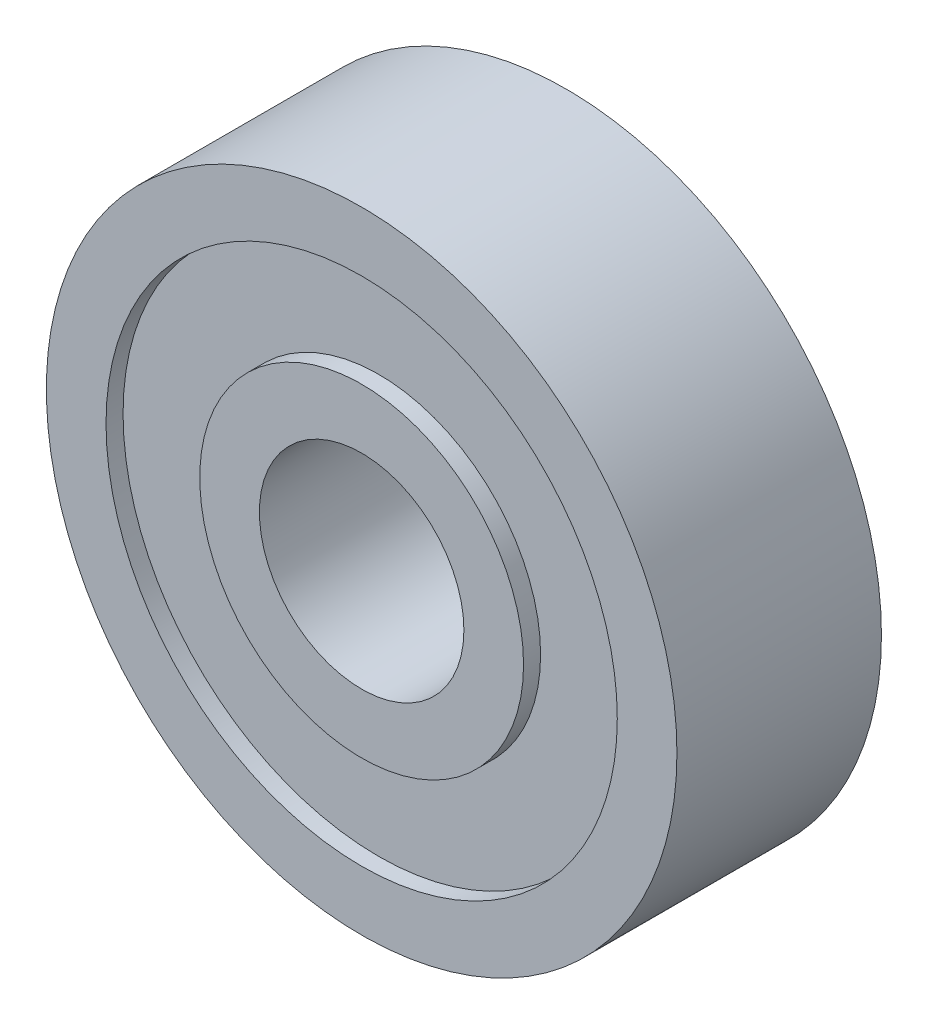
SolidWorks part; units mm, degrees
material "AISI Type 316L stainless steel"
ref_plane "Front Plane" through (0, 0, 0) normal (0, 0, 1) x (1, 0, 0)
ref_plane "Top Plane" through (0, 0, 0) normal (0, 1, 0) x (1, 0, 0)
ref_plane "Right Plane" through (0, 0, 0) normal (1, 0, 0) x (0, 0, -1)
sketch "Sketch1" plane through (0, 0, 0) normal (0, 0, 1) x (1, 0, 0)
  circle A1 centre (0, 0) radius 18.5
  dimension "D1" = 37
extrude "Boss-Extrude1" add sketch "Sketch1" along normal blind 12
sketch "Sketch2" plane through (0, 0, 12) normal (0, 0, 1) x (1, 0, 0)
  circle A0 centre (0, 0) radius 6
extrude "Cut-Extrude1" cut sketch "Sketch2" against normal blind 12
sketch "Sketch3" plane through (0, 0, 12) normal (0, 0, 1) x (1, 0, 0)
  circle A0 centre (0, 0) radius 15
  circle A1 centre (0, 0) radius 9.5
  circle A2 centre (0, 0) radius 18.5 construction
  circle A3 centre (0, 0) radius 6 construction
  dimension "D1" = 3.5
  dimension "D2" = 3.5
extrude "Cut-Extrude2" cut sketch "Sketch3" against normal blind 1
sketch "Sketch4" plane through (0, 0, 0) normal (0, 0, -1) x (-1, 0, 0)
  circle A0 centre (0, 0) radius 15
  circle A1 centre (0, 0) radius 9.5
  circle A2 centre (0, 0) radius 18.5 construction
  circle A3 centre (0, 0) radius 6 construction
  dimension "D1" = 3.5
  dimension "D2" = 3.5
extrude "Cut-Extrude3" cut sketch "Sketch4" against normal blind 1
